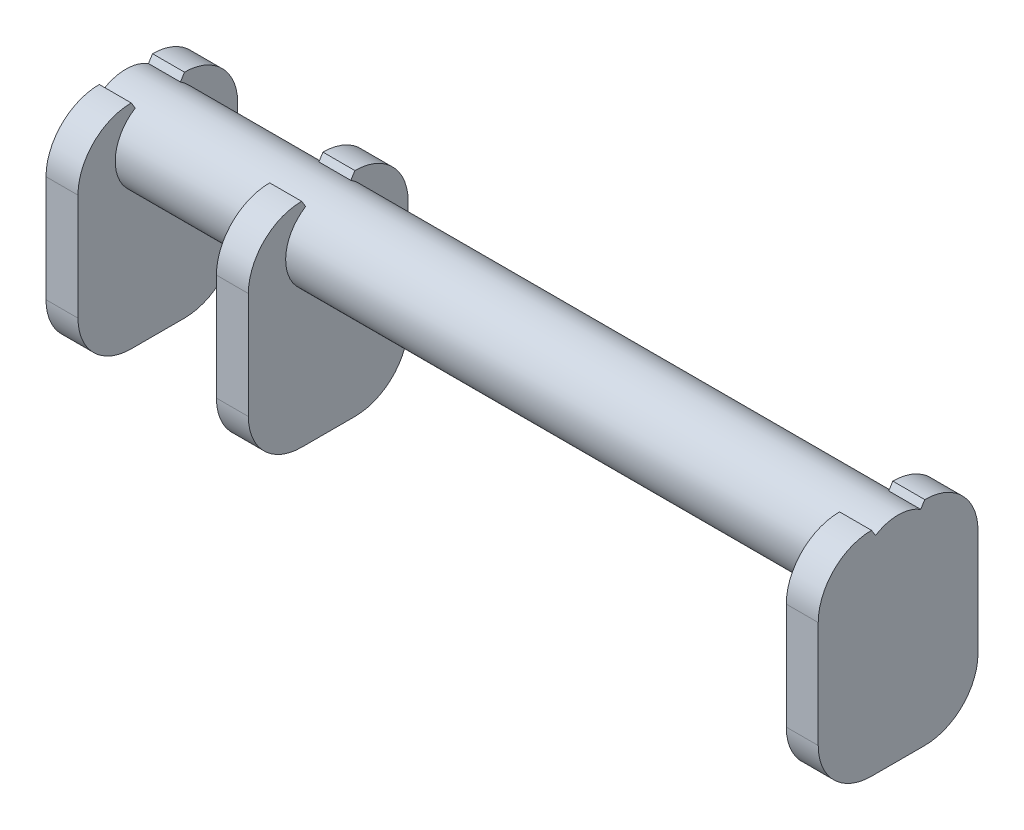
SolidWorks part; units mm, degrees
material "C40 or 38NiCrMo4"
ref_plane "Piano frontale" through (0, 0, 0) normal (0, 0, 1) x (1, 0, 0)
ref_plane "Piano superiore" through (0, 0, 0) normal (0, 1, 0) x (1, 0, 0)
ref_plane "Piano destro" through (0, 0, 0) normal (1, 0, 0) x (0, 0, -1)
sketch "Schizzo1" plane through (0, 0, 0) normal (1, 0, 0) x (0, 0, -1)
  circle A0 centre (0, 0) radius 8
  dimension "D1" = 16
extrude "Estrusione-Estrusione1" add sketch "Schizzo1" along normal blind 145
sketch "Schizzo2" plane through (0, 0, 0) normal (-1, 0, 0) x (0, 0, 1)
  line L0 (-1000, 0) -> (49000, 0) construction
  line L1 (0, -1000) -> (0, 49000) construction
  line L2 (-5, 8) -> (5, 8)
  line L3 (15, -2) -> (15, -22)
  line L4 (5, -32) -> (-5, -32)
  line L5 (-15, -2) -> (-15, -22)
  arc A0 (15, -22) -> (5, -32) centre (5, -22) cw
  arc A1 (5, 8) -> (15, -2) centre (5, -2) cw
  arc A2 (-5, 8) -> (-15, -2) centre (-5, -2) ccw
  arc A3 (-15, -22) -> (-5, -32) centre (-5, -22) ccw
  point P4 (-15, 8)
  point P9 (0, 8)
  point P11 (15, -32)
  point P14 (15, 8)
  point P21 (0, -32)
  point P22 (-15, -32)
  dimension "D4" = 10
  dimension "D1" = 8
  dimension "D2" = 15
  dimension "D3" = 40
extrude "Estrusione-Estrusione2" add sketch "Schizzo2" against normal blind 6
pattern_linear "Ripetizione a L1" count 2 spacing 32 along (1, 0, 0) of "Estrusione-Estrusione2"
pattern_linear "Ripetizione a L2" count 2 spacing 139 along (1, 0, 0) of "Estrusione-Estrusione2"
sketch "Sketch1" plane through (0, 0, 0) normal (-1, 0, 0) x (0, 0, 1)
  line L0 (-5, 8) -> (-4.24, 6.784)
  line L1 (5, 8) -> (4.24, 6.784)
  line L3 (-5, 8) -> (-5, 8.5026)
  line L4 (-5, 8.5026) -> (5, 8.5026)
  line L5 (5, 8.5026) -> (5, 8)
  circle A0 centre (0, 0) radius 8 construction
  arc A1 (4.24, 6.784) -> (-4.24, 6.784) centre (0, 0) ccw
extrude "Extrude2" cut sketch "Sketch1" against normal through all
